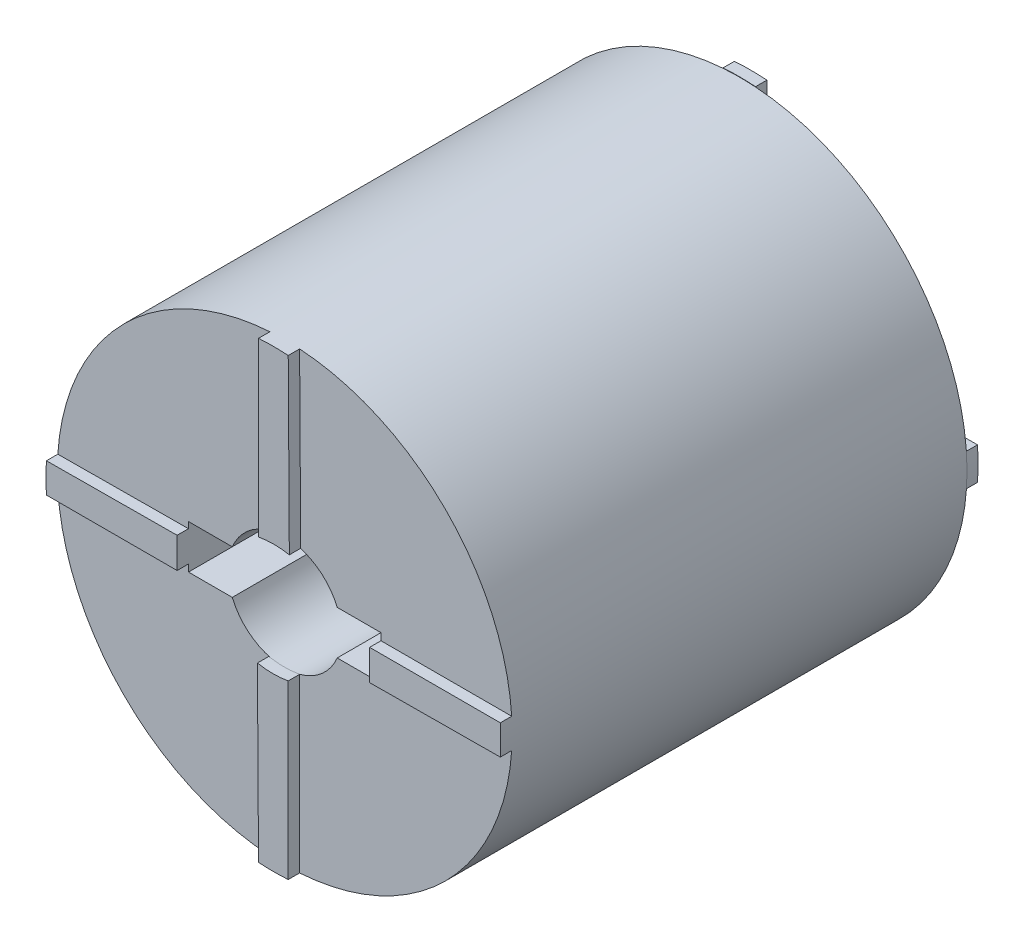
SolidWorks part; units mm, degrees
ref_plane "Front Plane" through (0, 0, 0) normal (0, 0, 1) x (1, 0, 0)
ref_plane "Top Plane" through (0, 0, 0) normal (0, 1, 0) x (1, 0, 0)
ref_plane "Right Plane" through (0, 0, 0) normal (1, 0, 0) x (0, 0, -1)
sketch "Sketch1" plane through (0, 0, 0) normal (0, 0, 1) x (1, 0, 0)
  circle A0 centre (0, 0) radius 40
  dimension "D1" = 80
extrude "Boss-Extrude1" add sketch "Sketch1" against normal blind 80
sketch "Sketch2" plane through (0, 0, 0) normal (0, 0, 1) x (1, 0, 0)
  circle A0 centre (0, 0) radius 10
  dimension "D1" = 20
extrude "Cut-Extrude1" cut sketch "Sketch2" against normal blind 50
sketch "Sketch5" plane through (0, 0, -80) normal (0, 0, -1) x (-1, 0, 0)
  line L0 (-2.806, 39.9533) -> (-2.806, 9.6375)
  line L1 (2.9176, 39.9533) -> (2.9176, 9.6375)
  line L2 (39.9533, 2.9176) -> (9.6375, 2.9176)
  line L3 (39.9533, -2.806) -> (9.6375, -2.806)
  line L4 (2.9176, -39.8417) -> (2.9176, -9.5259)
  line L5 (-2.806, -39.8417) -> (-2.806, -9.5259)
  line L6 (-39.8417, -2.806) -> (-9.5259, -2.806)
  line L7 (-39.8417, 2.9176) -> (-9.5259, 2.9176)
  arc A0 (-2.806, 39.9533) -> (2.9176, 39.9533) centre (0.0558, 0.0558) cw
  arc A1 (2.9176, 9.6375) -> (-2.806, 9.6375) centre (0.0558, 0.0558) ccw
  arc A2 (9.6375, -2.806) -> (9.6375, 2.9176) centre (0.0558, 0.0558) ccw
  arc A3 (39.9533, 2.9176) -> (39.9533, -2.806) centre (0.0558, 0.0558) cw
  arc A4 (-2.806, -9.5259) -> (2.9176, -9.5259) centre (0.0558, 0.0558) ccw
  arc A5 (2.9176, -39.8417) -> (-2.806, -39.8417) centre (0.0558, 0.0558) cw
  arc A6 (-9.5259, 2.9176) -> (-9.5259, -2.806) centre (0.0558, 0.0558) ccw
  arc A7 (-39.8417, -2.806) -> (-39.8417, 2.9176) centre (0.0558, 0.0558) cw
extrude "Boss-Extrude3" add sketch "Sketch5" along normal blind 2
sketch "Sketch7" plane through (0, 0, -50) normal (0, 0, 1) x (1, 0, 0)
  circle A0 centre (0, 0) radius 10
extrude "Cut-Extrude2" cut sketch "Sketch7" against normal blind 40
sketch "Sketch10" plane through (0, 0, 0) normal (0, 0, 1) x (1, 0, 0)
  line L0 (9.2292, 3.85) -> (16.9292, 3.85)
  line L1 (9.2292, -3.85) -> (16.9292, -3.85)
  line L2 (16.9292, -3.85) -> (16.9292, 3.85)
  line L3 (-9.2292, -3.85) -> (-16.9292, -3.85)
  line L4 (-16.9292, 3.85) -> (-16.9292, -3.85)
  line L5 (-9.2292, 3.85) -> (-16.9292, 3.85)
  circle A0 centre (0, 0) radius 10 construction
  arc A1 (9.2292, 3.85) -> (9.2292, -3.85) centre (0, 0) cw
  circle M5 centre (0, 0) radius 10
  dimension "D1" = 7.7
  dimension "D2" = 7.7
  dimension "D3" = 7.7
  dimension "D4" = 2
extrude "Cut-Extrude3" cut sketch "Sketch10" against normal blind 86 contours L5 L4 L3 M5 | L1 L2 L0 M5
sketch "Sketch12" plane through (0, 0, 0) normal (0, 0, 1) x (1, 0, 0)
  line L0 (-2.6139, 39.9145) -> (-2.6139, 9.6523)
  line L1 (2.6139, 39.9145) -> (2.806, 9.6375)
  line L2 (39.9145, 2.6139) -> (9.6523, 2.6139)
  line L3 (39.9145, -2.6139) -> (9.6375, -2.806)
  line L4 (2.6139, -39.9145) -> (2.6139, -9.6523)
  line L5 (-2.6139, -39.9145) -> (-2.806, -9.6375)
  line L6 (-39.9145, -2.6139) -> (-9.6523, -2.6139)
  line L7 (-39.9145, 2.6139) -> (-9.6375, 2.806)
  circle A1 centre (0, 0) radius 40 construction
  arc A2 (9.2292, 3.85) -> (-9.2292, 3.85) centre (0, 0) ccw construction
  arc A3 (-2.6139, 39.9145) -> (2.6139, 39.9145) centre (0, 0) cw
  arc A4 (-2.6139, 9.6523) -> (2.806, 9.6375) centre (0.0569, -4.6948) cw
  arc A5 (9.6523, 2.6139) -> (9.6375, -2.806) centre (-4.6948, -0.0569) cw
  arc A6 (39.9145, 2.6139) -> (39.9145, -2.6139) centre (0, 0) cw
  arc A7 (2.6139, -9.6523) -> (-2.806, -9.6375) centre (-0.0569, 4.6948) cw
  arc A8 (2.6139, -39.9145) -> (-2.6139, -39.9145) centre (0, 0) cw
  arc A9 (-9.6523, -2.6139) -> (-9.6375, 2.806) centre (4.6948, 0.0569) cw
  arc A10 (-39.9145, -2.6139) -> (-39.9145, 2.6139) centre (0, 0) cw
  dimension "D1" = 4
extrude "Boss-Extrude5" add sketch "Sketch12" along normal blind 2
sketch "Sketch14" plane through (0, 0, 2) normal (0, 0, 1) x (1, 0, 0)
  line L1 (-16.9292, 3.85) -> (16.9292, 3.85)
  line L2 (-16.9292, 3.85) -> (-16.9292, -3.85)
  line L3 (-16.9292, -3.85) -> (16.9292, -3.85)
  line L4 (16.9292, 3.85) -> (16.9292, -3.85)
extrude "Cut-Extrude6" cut sketch "Sketch14" against normal blind 9
